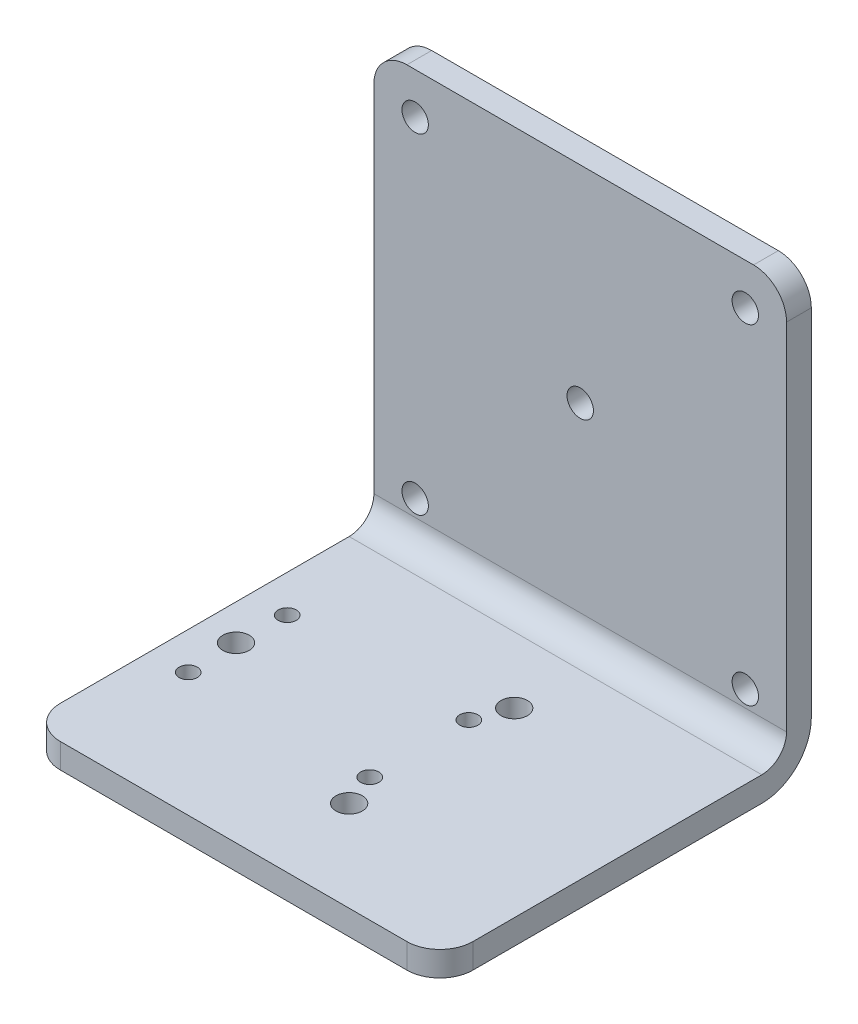
SolidWorks part; units mm, degrees
ref_plane "Front Plane" through (0, 0, 0) normal (0, 0, 1) x (1, 0, 0)
ref_plane "Top Plane" through (0, 0, 0) normal (0, 1, 0) x (1, 0, 0)
ref_plane "Right Plane" through (0, 0, 0) normal (1, 0, 0) x (0, 0, -1)
sketch "Sketch1" plane through (0, 0, 0) normal (0, 1, 0) x (1, 0, 0)
  line L1 (-25, -22.5) -> (25, -22.5)
  line L2 (-25, -22.5) -> (-25, 22.5)
  line L3 (-25, 22.5) -> (25, 22.5)
  line L4 (25, -22.5) -> (25, 22.5)
  line L5 (-25, -22.5) -> (25, 22.5) construction
  line L6 (-25, 22.5) -> (25, -22.5) construction
  point P0 (0, 0)
  dimension "D1" = 50
  dimension "D2" = 45
extrude "Boss-Extrude1" add sketch "Sketch1" along normal blind 3
sketch "Sketch2" plane through (0, 3, 0) normal (0, 1, 0) x (1, 0, 0)
  line L0 (25, -22.5) -> (25, 22.5) construction
  line L1 (-25, 22.5) -> (25, 22.5)
  line L2 (-25, 22.5) -> (-25, 19.5)
  line L3 (-25, 19.5) -> (25, 19.5)
  line L4 (25, 22.5) -> (25, 19.5)
  dimension "D1" = 3
extrude "Boss-Extrude2" add sketch "Sketch2" along normal blind 50
sketch "Sketch3" plane through (0, 3, 0) normal (0, 1, 0) x (1, 0, 0)
  line L0 (-25, -1.5) -> (25, -1.5) construction
  line L3 (-25, 19.5) -> (-25, -22.5) construction
  line L4 (25, -22.5) -> (25, 19.5) construction
  line L5 (18, 42.7187) -> (18, -42.7973) construction
  circle A2 centre (3, 8.5) radius 1.6
  circle A3 centre (3, -11.5) radius 1.6
  circle A4 centre (-20.7, -1.5) radius 1.6
  circle A5 centre (1.5, 4.5) radius 1.1
  circle A6 centre (1.5, -7.5) radius 1.1
  circle A7 centre (-20.5, 4.5) radius 1.1
  circle A8 centre (-20.5, -7.5) radius 1.1
  dimension "D2" = 3.2
  dimension "D5" = 3.2
  dimension "D9" = 2.2
  dimension "D3" = 15
  dimension "D4" = 10
  dimension "D6" = 23.7
  dimension "D7" = 16.5
  dimension "D8" = 6
  dimension "D10" = 22
  dimension "D11" = 7
extrude "Cut-Extrude1" cut sketch "Sketch3" against normal up to surface (3 mm away) up to face at (0, 0, 0)
sketch "Sketch4" plane through (0, 0, -19.5) normal (0, 0, 1) x (1, 0, 0)
  line L0 (25, 53) -> (25, 3) construction
  line L1 (-20, 48) -> (20, 48) construction
  line L2 (-20, 48) -> (-20, 8) construction
  line L3 (-20, 8) -> (20, 8) construction
  line L4 (20, 48) -> (20, 8) construction
  line L5 (-25, 53) -> (25, 53) construction
  line L6 (-20, 48) -> (20, 8) construction
  line L7 (20, 48) -> (-20, 8) construction
  circle A0 centre (-20, 48) radius 1.6
  circle A1 centre (20, 48) radius 1.6
  circle A2 centre (20, 8) radius 1.6
  circle A3 centre (-20, 8) radius 1.6
  circle A4 centre (0, 28) radius 1.6
  point P4 (20, 28)
  point P7 (25, 28)
  point P8 (0, 48)
  point P11 (0, 53)
  dimension "D2" = 3.2
  dimension "D1" = 40
extrude "Cut-Extrude2" cut sketch "Sketch4" against normal up to surface (3 mm away) up to face at (0, 26.5, -22.5)
fillet "Fillet1" radius 4 4 edges at (25, 53, -21) (-25, 53, -21) (25, 1.5, 22.5) (-25, 1.5, 22.5)
fillet "Fillet2" radius 3 1 edges at (0, 3, -19.5)
fillet "Fillet3" radius 6 1 edges at (0, 0, -22.5)
